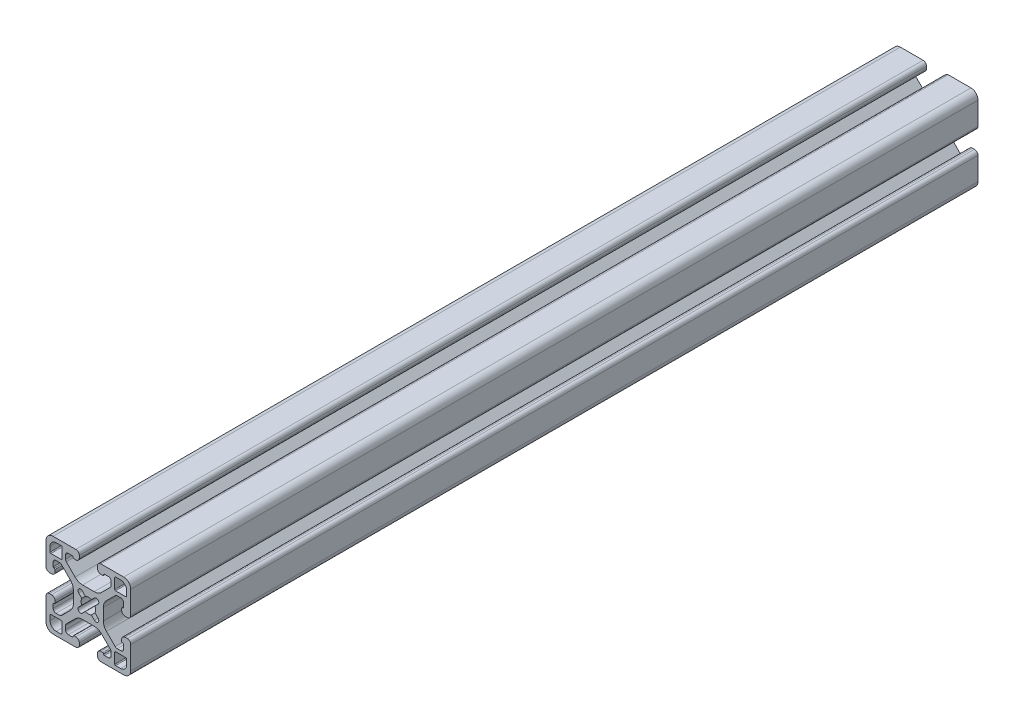
SolidWorks part; units mm, degrees
ref_plane "Front Plane" through (0, 0, 0) normal (0, 0, 1) x (1, 0, 0)
ref_plane "Top Plane" through (0, 0, 0) normal (0, 1, 0) x (1, 0, 0)
ref_plane "Right Plane" through (0, 0, 0) normal (1, 0, 0) x (0, 0, -1)
sketch "Sketch1" plane through (0, 0, 0) normal (0, 0, 1) x (1, 0, 0)
  line L0 (-66.7042, -2.4885) -> (-65.3338, -1.1181)
  line L1 (-65.3338, 1.5948) -> (-66.7042, 2.9652)
  line L2 (-65.0878, 4.5817) -> (-63.7174, 3.2113)
  line L3 (-61.0045, 3.2113) -> (-59.7212, 4.484)
  line L4 (-58.1153, 2.8781) -> (-59.3881, 1.5948)
  line L5 (-59.3881, -1.1181) -> (-58.0176, -2.4885)
  line L6 (-59.6341, -4.1049) -> (-61.0045, -2.7345)
  line L7 (-63.7174, -2.7345) -> (-65.0878, -4.1049)
  line L8 (-79.6075, 12.4812) -> (-79.6075, 14.691)
  line L9 (-76.8135, 17.485) -> (-74.6037, 17.485)
  line L10 (-74.2227, 17.104) -> (-74.2227, 12.4812)
  line L11 (-74.6037, 12.1002) -> (-79.2265, 12.1002)
  line L12 (-74.6037, -17.0082) -> (-76.8135, -17.0082)
  line L13 (-79.6075, -14.2142) -> (-79.6075, -12.0044)
  line L14 (-79.2265, -11.6234) -> (-74.6037, -11.6234)
  line L15 (-74.2227, -12.0044) -> (-74.2227, -16.6272)
  line L16 (-45.1143, -12.0044) -> (-45.1143, -14.2142)
  line L17 (-47.9083, -17.0082) -> (-50.1181, -17.0082)
  line L18 (-50.4991, -16.6272) -> (-50.4991, -12.0044)
  line L19 (-50.1181, -11.6234) -> (-45.4953, -11.6234)
  line L20 (-50.1181, 17.485) -> (-47.9083, 17.485)
  line L21 (-45.1143, 14.691) -> (-45.1143, 12.4812)
  line L22 (-45.4953, 12.1002) -> (-50.1181, 12.1002)
  line L23 (-50.4991, 12.4812) -> (-50.4991, 17.104)
  line L24 (-46.5368, -7.0006) -> (-46.5368, -8.7746)
  line L25 (-47.8067, -10.0486) -> (-49.3926, -10.0486)
  line L26 (-50.2907, -9.6767) -> (-54.2388, -5.7286)
  line L27 (-55.6299, -2.3699) -> (-55.6299, 2.8467)
  line L28 (-54.2388, 6.2053) -> (-50.2907, 10.1534)
  line L29 (-49.3926, 10.5254) -> (-47.8067, 10.5254)
  line L30 (-46.5368, 9.2513) -> (-46.5368, 7.4774)
  line L31 (-46.9178, 7.0964) -> (-46.994, 7.0964)
  line L32 (-47.375, 6.7154) -> (-47.3749, 5.8772)
  line L33 (-45.8001, 4.3024) -> (-44.8857, 4.3024)
  line L34 (-43.3109, 5.8772) -> (-43.3109, 16.1134)
  line L35 (-46.4859, 19.2884) -> (-56.7221, 19.2884)
  line L36 (-58.2969, 17.7136) -> (-58.2969, 16.7992)
  line L37 (-56.7222, 15.2244) -> (-55.884, 15.2244)
  line L38 (-55.503, 15.6054) -> (-55.503, 15.6816)
  line L39 (-55.122, 16.0626) -> (-53.348, 16.0626)
  line L40 (-52.0739, 14.7926) -> (-52.0739, 13.2067)
  line L41 (-52.4459, 12.3087) -> (-56.394, 8.3606)
  line L42 (-59.7526, 6.9694) -> (-64.9693, 6.9694)
  line L43 (-68.3279, 8.3606) -> (-72.276, 12.3087)
  line L44 (-72.6479, 13.2067) -> (-72.6479, 14.7926)
  line L45 (-71.3739, 16.0626) -> (-69.5999, 16.0626)
  line L46 (-69.2189, 15.6816) -> (-69.2189, 15.6054)
  line L47 (-68.8379, 15.2244) -> (-67.9997, 15.2244)
  line L48 (-66.4249, 16.7992) -> (-66.4249, 17.7136)
  line L49 (-67.9997, 19.2884) -> (-78.2359, 19.2884)
  line L50 (-81.4109, 16.1134) -> (-81.4109, 5.8772)
  line L51 (-79.8361, 4.3024) -> (-78.9217, 4.3024)
  line L52 (-77.3469, 5.8772) -> (-77.3469, 6.7154)
  line L53 (-77.7279, 7.0964) -> (-77.8041, 7.0964)
  line L54 (-78.1851, 7.4774) -> (-78.1851, 9.2513)
  line L55 (-76.9151, 10.5254) -> (-75.3293, 10.5254)
  line L56 (-74.4312, 10.1534) -> (-70.4831, 6.2053)
  line L57 (-69.0919, 2.8467) -> (-69.0919, -2.3699)
  line L58 (-70.4831, -5.7286) -> (-74.4312, -9.6767)
  line L59 (-75.3293, -10.0486) -> (-76.9151, -10.0486)
  line L60 (-78.1851, -8.7746) -> (-78.1851, -7.0006)
  line L61 (-77.8041, -6.6196) -> (-77.7279, -6.6196)
  line L62 (-77.3469, -6.2386) -> (-77.3469, -5.4004)
  line L63 (-78.9217, -3.8256) -> (-79.8361, -3.8256)
  line L64 (-81.4109, -5.4004) -> (-81.4109, -15.6366)
  line L65 (-78.2359, -18.8116) -> (-67.9997, -18.8116)
  line L66 (-66.4249, -17.2368) -> (-66.4249, -16.3224)
  line L67 (-67.9997, -14.7476) -> (-68.8379, -14.7476)
  line L68 (-69.2189, -15.1286) -> (-69.2189, -15.2048)
  line L69 (-69.5999, -15.5858) -> (-71.3739, -15.5858)
  line L70 (-72.6479, -14.3158) -> (-72.6479, -12.7299)
  line L71 (-72.276, -11.8319) -> (-68.3279, -7.8838)
  line L72 (-64.9693, -6.4926) -> (-59.7526, -6.4926)
  line L73 (-56.394, -7.8838) -> (-52.4459, -11.8319)
  line L74 (-52.0739, -12.7299) -> (-52.0739, -14.3158)
  line L75 (-53.348, -15.5858) -> (-55.122, -15.5858)
  line L76 (-55.503, -15.2048) -> (-55.503, -15.1286)
  line L77 (-55.884, -14.7476) -> (-56.7222, -14.7476)
  line L78 (-58.2969, -16.3224) -> (-58.2969, -17.2368)
  line L79 (-56.7221, -18.8116) -> (-46.4859, -18.8116)
  line L80 (-43.3109, -15.6366) -> (-43.3109, -5.4004)
  line L81 (-44.8857, -3.8256) -> (-45.8001, -3.8256)
  line L82 (-47.3749, -5.4004) -> (-47.375, -6.2386)
  line L83 (-46.994, -6.6196) -> (-46.9178, -6.6196)
  arc A0 (-66.7042, -2.4885) -> (-65.0878, -4.1049) centre (-65.896, -3.2967) ccw
  arc A1 (-65.3338, 1.5948) -> (-65.3338, -1.1181) centre (-62.3609, 0.2384) ccw
  arc A2 (-65.0878, 4.5817) -> (-66.7042, 2.9652) centre (-65.896, 3.7734) ccw
  arc A3 (-61.0045, 3.2113) -> (-63.7174, 3.2113) centre (-62.3609, 0.2384) ccw
  arc A4 (-58.1153, 2.8781) -> (-59.7212, 4.484) centre (-58.8259, 3.7734) ccw
  arc A5 (-59.3881, -1.1181) -> (-59.3881, 1.5948) centre (-62.3609, 0.2384) ccw
  arc A6 (-59.6341, -4.1049) -> (-58.0176, -2.4885) centre (-58.8259, -3.2967) ccw
  arc A7 (-63.7174, -2.7345) -> (-61.0045, -2.7345) centre (-62.3609, 0.2384) ccw
  arc A8 (-79.6075, 12.4812) -> (-79.2265, 12.1002) centre (-79.2265, 12.4812) ccw
  arc A9 (-76.8135, 17.485) -> (-79.6075, 14.691) centre (-76.8135, 14.691) ccw
  arc A10 (-74.2227, 17.104) -> (-74.6037, 17.485) centre (-74.6037, 17.104) ccw
  arc A11 (-74.6037, 12.1002) -> (-74.2227, 12.4812) centre (-74.6037, 12.4812) ccw
  arc A12 (-74.6037, -17.0082) -> (-74.2227, -16.6272) centre (-74.6037, -16.6272) ccw
  arc A13 (-79.6075, -14.2142) -> (-76.8135, -17.0082) centre (-76.8135, -14.2142) ccw
  arc A14 (-79.2265, -11.6234) -> (-79.6075, -12.0044) centre (-79.2265, -12.0044) ccw
  arc A15 (-74.2227, -12.0044) -> (-74.6037, -11.6234) centre (-74.6037, -12.0044) ccw
  arc A16 (-45.1143, -12.0044) -> (-45.4953, -11.6234) centre (-45.4953, -12.0044) ccw
  arc A17 (-47.9083, -17.0082) -> (-45.1143, -14.2142) centre (-47.9083, -14.2142) ccw
  arc A18 (-50.4991, -16.6272) -> (-50.1181, -17.0082) centre (-50.1181, -16.6272) ccw
  arc A19 (-50.1181, -11.6234) -> (-50.4991, -12.0044) centre (-50.1181, -12.0044) ccw
  arc A20 (-50.1181, 17.485) -> (-50.4991, 17.104) centre (-50.1181, 17.104) ccw
  arc A21 (-45.1143, 14.691) -> (-47.9083, 17.485) centre (-47.9083, 14.691) ccw
  arc A22 (-45.4953, 12.1002) -> (-45.1143, 12.4812) centre (-45.4953, 12.4812) ccw
  arc A23 (-50.4991, 12.4812) -> (-50.1181, 12.1002) centre (-50.1181, 12.4812) ccw
  arc A24 (-47.8067, -10.0486) -> (-46.5368, -8.7746) centre (-47.8067, -8.7786) ccw
  arc A25 (-50.2907, -9.6767) -> (-49.3926, -10.0486) centre (-49.3926, -8.7786) ccw
  arc A26 (-55.6299, -2.3699) -> (-54.2388, -5.7286) centre (-50.8801, -2.3699) ccw
  arc A27 (-54.2388, 6.2053) -> (-55.6299, 2.8467) centre (-50.8801, 2.8467) ccw
  arc A28 (-49.3926, 10.5254) -> (-50.2907, 10.1534) centre (-49.3926, 9.2554) ccw
  arc A29 (-46.5368, 9.2513) -> (-47.8067, 10.5254) centre (-47.8067, 9.2554) ccw
  arc A30 (-46.9178, 7.0964) -> (-46.5368, 7.4774) centre (-46.9178, 7.4774) ccw
  arc A31 (-46.994, 7.0964) -> (-47.375, 6.7154) centre (-46.994, 6.7154) ccw
  arc A32 (-47.3749, 5.8772) -> (-45.8001, 4.3024) centre (-45.8001, 5.8772) ccw
  arc A33 (-44.8857, 4.3024) -> (-43.3109, 5.8772) centre (-44.8857, 5.8772) ccw
  arc A34 (-43.3109, 16.1134) -> (-46.4859, 19.2884) centre (-46.4859, 16.1134) ccw
  arc A35 (-56.7221, 19.2884) -> (-58.2969, 17.7136) centre (-56.7221, 17.7136) ccw
  arc A36 (-58.2969, 16.7992) -> (-56.7222, 15.2244) centre (-56.7221, 16.7992) ccw
  arc A37 (-55.884, 15.2244) -> (-55.503, 15.6054) centre (-55.884, 15.6054) ccw
  arc A38 (-55.122, 16.0626) -> (-55.503, 15.6816) centre (-55.122, 15.6816) ccw
  arc A39 (-52.0739, 14.7926) -> (-53.348, 16.0626) centre (-53.3439, 14.7926) ccw
  arc A40 (-52.4459, 12.3087) -> (-52.0739, 13.2067) centre (-53.3439, 13.2067) ccw
  arc A41 (-59.7526, 6.9694) -> (-56.394, 8.3606) centre (-59.7526, 11.7192) ccw
  arc A42 (-68.3279, 8.3606) -> (-64.9693, 6.9694) centre (-64.9693, 11.7192) ccw
  arc A43 (-72.6479, 13.2067) -> (-72.276, 12.3087) centre (-71.3779, 13.2067) ccw
  arc A44 (-71.3739, 16.0626) -> (-72.6479, 14.7926) centre (-71.3779, 14.7926) ccw
  arc A45 (-69.2189, 15.6816) -> (-69.5999, 16.0626) centre (-69.5999, 15.6816) ccw
  arc A46 (-69.2189, 15.6054) -> (-68.8379, 15.2244) centre (-68.8379, 15.6054) ccw
  arc A47 (-67.9997, 15.2244) -> (-66.4249, 16.7992) centre (-67.9997, 16.7992) ccw
  arc A48 (-66.4249, 17.7136) -> (-67.9997, 19.2884) centre (-67.9997, 17.7136) ccw
  arc A49 (-78.2359, 19.2884) -> (-81.4109, 16.1134) centre (-78.2359, 16.1134) ccw
  arc A50 (-81.4109, 5.8772) -> (-79.8361, 4.3024) centre (-79.8361, 5.8772) ccw
  arc A51 (-78.9217, 4.3024) -> (-77.3469, 5.8772) centre (-78.9217, 5.8772) ccw
  arc A52 (-77.3469, 6.7154) -> (-77.7279, 7.0964) centre (-77.7279, 6.7154) ccw
  arc A53 (-78.1851, 7.4774) -> (-77.8041, 7.0964) centre (-77.8041, 7.4774) ccw
  arc A54 (-76.9151, 10.5254) -> (-78.1851, 9.2513) centre (-76.9151, 9.2554) ccw
  arc A55 (-74.4312, 10.1534) -> (-75.3293, 10.5254) centre (-75.3293, 9.2554) ccw
  arc A56 (-69.0919, 2.8467) -> (-70.4831, 6.2053) centre (-73.8417, 2.8467) ccw
  arc A57 (-70.4831, -5.7286) -> (-69.0919, -2.3699) centre (-73.8417, -2.3699) ccw
  arc A58 (-75.3293, -10.0486) -> (-74.4312, -9.6767) centre (-75.3293, -8.7786) ccw
  arc A59 (-78.1851, -8.7746) -> (-76.9151, -10.0486) centre (-76.9151, -8.7786) ccw
  arc A60 (-77.8041, -6.6196) -> (-78.1851, -7.0006) centre (-77.8041, -7.0006) ccw
  arc A61 (-77.7279, -6.6196) -> (-77.3469, -6.2386) centre (-77.7279, -6.2386) ccw
  arc A62 (-77.3469, -5.4004) -> (-78.9217, -3.8256) centre (-78.9217, -5.4004) ccw
  arc A63 (-79.8361, -3.8256) -> (-81.4109, -5.4004) centre (-79.8361, -5.4004) ccw
  arc A64 (-81.4109, -15.6366) -> (-78.2359, -18.8116) centre (-78.2359, -15.6366) ccw
  arc A65 (-67.9997, -18.8116) -> (-66.4249, -17.2368) centre (-67.9997, -17.2368) ccw
  arc A66 (-66.4249, -16.3224) -> (-67.9997, -14.7476) centre (-67.9997, -16.3224) ccw
  arc A67 (-68.8379, -14.7476) -> (-69.2189, -15.1286) centre (-68.8379, -15.1286) ccw
  arc A68 (-69.5999, -15.5858) -> (-69.2189, -15.2048) centre (-69.5999, -15.2048) ccw
  arc A69 (-72.6479, -14.3158) -> (-71.3739, -15.5858) centre (-71.3779, -14.3158) ccw
  arc A70 (-72.276, -11.8319) -> (-72.6479, -12.7299) centre (-71.3779, -12.7299) ccw
  arc A71 (-64.9693, -6.4926) -> (-68.3279, -7.8838) centre (-64.9693, -11.2424) ccw
  arc A72 (-56.394, -7.8838) -> (-59.7526, -6.4926) centre (-59.7526, -11.2424) ccw
  arc A73 (-52.0739, -12.7299) -> (-52.4459, -11.8319) centre (-53.3439, -12.7299) ccw
  arc A74 (-53.348, -15.5858) -> (-52.0739, -14.3158) centre (-53.3439, -14.3158) ccw
  arc A75 (-55.503, -15.2048) -> (-55.122, -15.5858) centre (-55.122, -15.2048) ccw
  arc A76 (-55.503, -15.1286) -> (-55.884, -14.7476) centre (-55.884, -15.1286) ccw
  arc A77 (-56.7222, -14.7476) -> (-58.2969, -16.3224) centre (-56.7221, -16.3224) ccw
  arc A78 (-58.2969, -17.2368) -> (-56.7221, -18.8116) centre (-56.7221, -17.2368) ccw
  arc A79 (-46.4859, -18.8116) -> (-43.3109, -15.6366) centre (-46.4859, -15.6366) ccw
  arc A80 (-43.3109, -5.4004) -> (-44.8857, -3.8256) centre (-44.8857, -5.4004) ccw
  arc A81 (-45.8001, -3.8256) -> (-47.3749, -5.4004) centre (-45.8001, -5.4004) ccw
  arc A82 (-47.375, -6.2386) -> (-46.994, -6.6196) centre (-46.994, -6.2386) ccw
  arc A83 (-46.5368, -7.0006) -> (-46.9178, -6.6196) centre (-46.9178, -7.0006) ccw
extrude "Extrude1" add sketch "Sketch1" against normal blind 381
